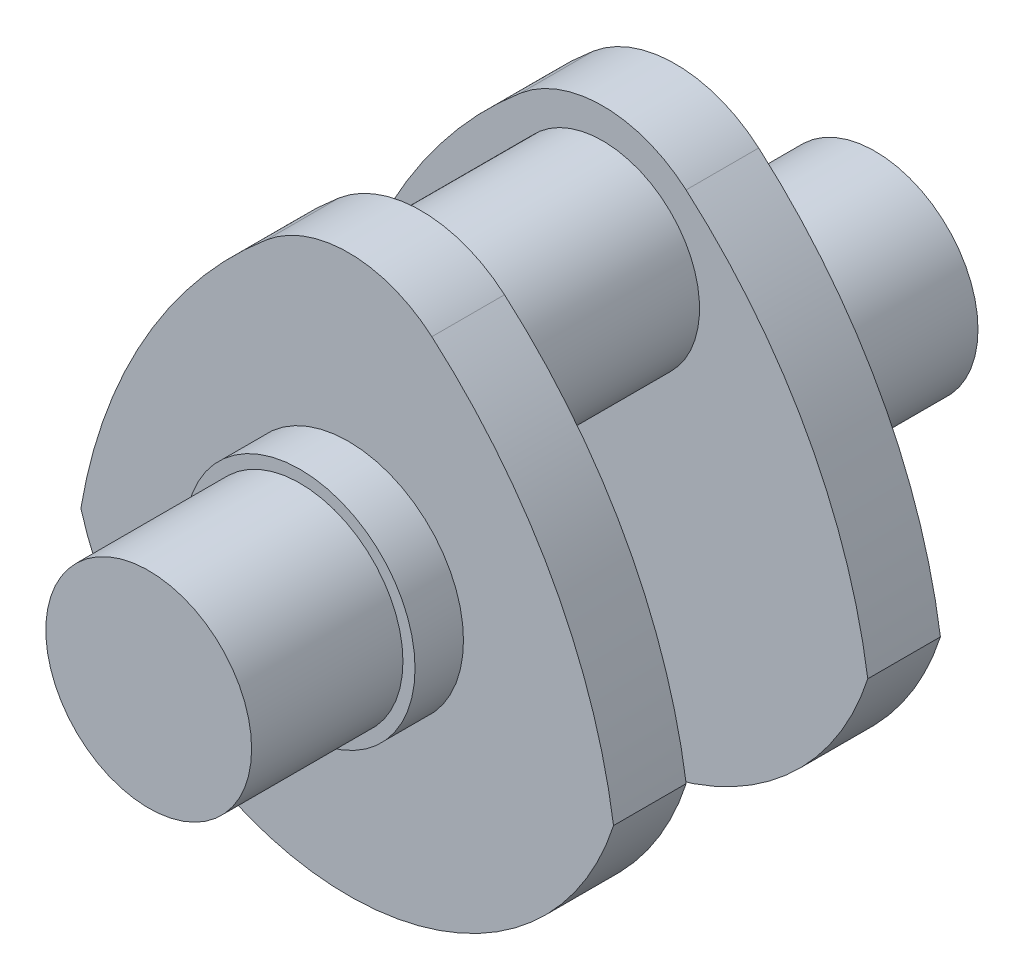
SolidWorks part; units mm, degrees
material "Cast Carbon Steel"
ref_plane "Front Plane" through (0, 0, 0) normal (0, 0, 1) x (1, 0, 0)
ref_plane "Top Plane" through (0, 0, 0) normal (0, 1, 0) x (1, 0, 0)
ref_plane "Right Plane" through (0, 0, 0) normal (1, 0, 0) x (0, 0, -1)
sketch "Sketch1" plane through (0, 0, 0) normal (0, 0, 1) x (1, 0, 0)
  circle A0 centre (0, 0) radius 17
  dimension "D1" = 34
extrude "Boss-Extrude1" add sketch "Sketch1" along normal blind 25
sketch "Sketch2" plane through (0, 0, 0) normal (0, 0, -1) x (-1, 0, 0)
  circle A0 centre (0, 0) radius 19
  dimension "D1" = 38
extrude "Boss-Extrude2" add sketch "Sketch2" along normal blind 8
sketch "Sketch3" plane through (0, 0, -8) normal (0, 0, -1) x (-1, 0, 0)
  arc A0 (-43.7904, -14.0854) -> (-13.777, 40.8491) centre (45.2671, -27.0758) cw
  arc A1 (13.5533, 41.0409) -> (44.2096, -12.7088) centre (-44.5322, -27.7057) cw
  arc A2 (-43.7904, -14.0854) -> (44.2096, -12.7088) centre (0, 0) ccw
  arc A3 (-13.777, 40.8491) -> (13.5533, 41.0409) centre (0, 25) cw
  point P7 (39.496, 132.9018)
  point P8 (0, 0)
  point P9 (43.1412, -15.9637)
  point P10 (-44.5322, -12.7088)
  dimension "D1" = 90
  dimension "D2" = 90
  dimension "D4" = 46
  dimension "D5" = 21
  dimension "D3" = 88
  dimension "D6" = 25
extrude "Boss-Extrude3" add sketch "Sketch3" along normal blind 12
sketch "Sketch4" plane through (0, 0, -20) normal (0, 0, -1) x (-1, 0, 0)
  circle A0 centre (0, 25) radius 16
  point P2 (0, 0)
  dimension "D2" = 32
  dimension "D1" = 25
extrude "Boss-Extrude4" add sketch "Sketch4" along normal blind 15
mirror "Mirror1" about plane through (0, 25, -35) normal (0, 0, -1) of bodies 104
